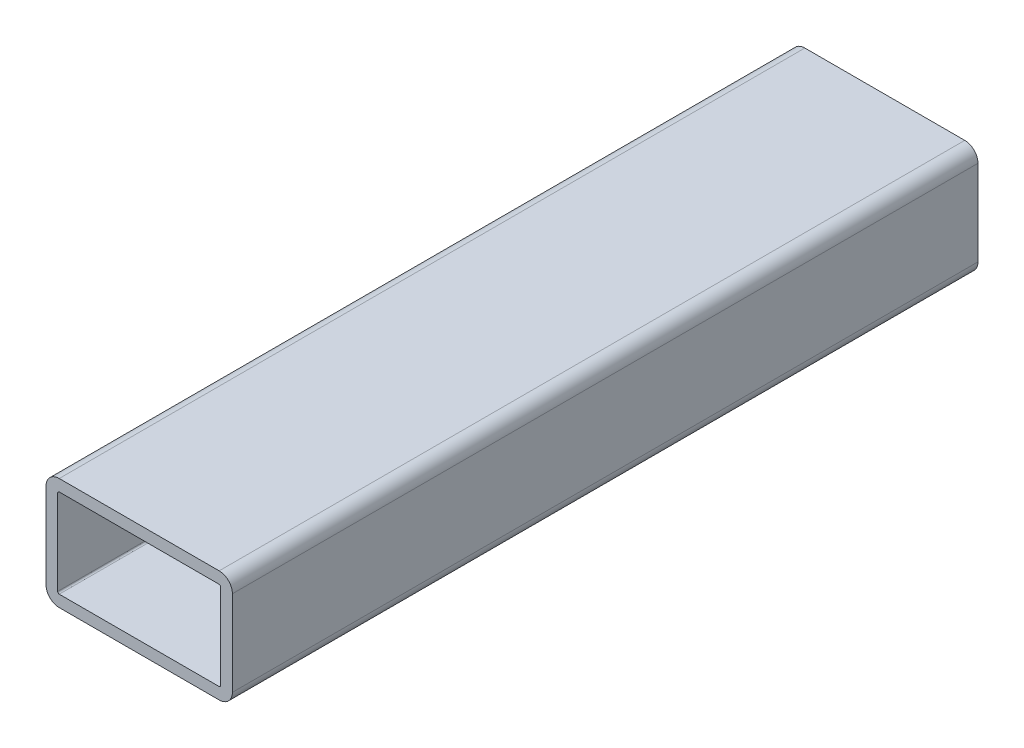
SolidWorks part; units mm, degrees
ref_plane "Front Plane" through (0, 0, 0) normal (0, 0, 1) x (1, 0, 0)
ref_plane "Top Plane" through (0, 0, 0) normal (0, 1, 0) x (1, 0, 0)
ref_plane "Right Plane" through (0, 0, 0) normal (1, 0, 0) x (0, 0, -1)
sketch3d "3DSketch3"
  line L0 (0, 0, -400) -> (0, 0, 400)
  point P4 (0, 0, 0)
  dimension "D1" = 800
other "Tube square TS12X12X0.25(1)"
ref_plane "Plane13" through (0, 0, -400) normal (0, 0, 1) x (0, 1, 0)
sketch "Sketch165" plane through (0, 0, -400) normal (0, 0, 1) x (0, 1, 0)
  line L0 (-45.8, -87.5) -> (45.8, -87.5)
  line L1 (-47.5, -85.8) -> (-47.5, 85.8)
  line L2 (45.8, 87.5) -> (-45.8, 87.5)
  line L3 (47.5, 85.8) -> (47.5, -85.8)
  line L4 (-45.8, -100) -> (45.8, -100)
  line L5 (-60, -85.8) -> (-60, 85.8)
  line L6 (45.8, 100) -> (-45.8, 100)
  line L7 (60, 85.8) -> (60, -85.8)
  line L8 (-60, 0) -> (-47.5, 0) construction
  line L9 (-47.5, 0) -> (47.5, 0) construction
  line L10 (47.5, 0) -> (60, 0) construction
  line L11 (0, 100) -> (0, 87.5) construction
  line L12 (0, 87.5) -> (0, -87.5) construction
  line L13 (0, -87.5) -> (0, -100) construction
  arc A0 (60, 85.8) -> (45.8, 100) centre (45.8, 85.8) ccw
  arc A1 (45.8, -100) -> (60, -85.8) centre (45.8, -85.8) ccw
  arc A2 (-60, -85.8) -> (-45.8, -100) centre (-45.8, -85.8) ccw
  arc A3 (-45.8, 100) -> (-60, 85.8) centre (-45.8, 85.8) ccw
  arc A4 (-45.8, 87.5) -> (-47.5, 85.8) centre (-45.8, 85.8) ccw
  arc A5 (47.5, 85.8) -> (45.8, 87.5) centre (45.8, 85.8) ccw
  arc A6 (45.8, -87.5) -> (47.5, -85.8) centre (45.8, -85.8) ccw
  arc A7 (-47.5, -85.8) -> (-45.8, -87.5) centre (-45.8, -85.8) ccw
  point P6 (-60, -100)
  point P33 (-60, 100)
  point P35 (60, 100)
  point P36 (60, -100)
  point P37 (0, 0)
  point P38 (0, 0)
  dimension "D1" = 200
  dimension "Thickness" = 12.5
  dimension "H_leg" = 120
